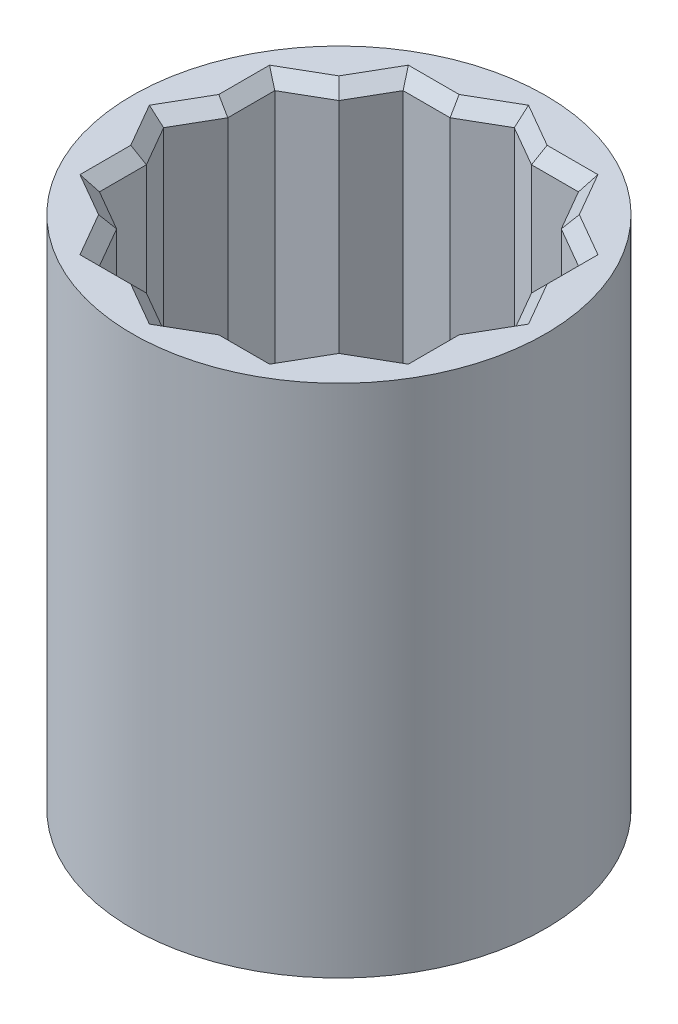
SolidWorks part; units mm, degrees
ref_plane "Front Plane" through (0, 0, 0) normal (0, 0, 1) x (1, 0, 0)
ref_plane "Top Plane" through (0, 0, 0) normal (0, 1, 0) x (1, 0, 0)
ref_plane "Right Plane" through (0, 0, 0) normal (1, 0, 0) x (0, 0, -1)
sketch "Sketch1" plane through (0, 0, 0) normal (0, 1, 0) x (1, 0, 0)
  circle A0 centre (0, 0) radius 9.779
  dimension "Socket_Diameter" = 19.558
extrude "Boss-Extrude1" add sketch "Sketch1" along normal blind 24.384
sketch "Sketch2" plane through (0, 0, 0) normal (0, -1, 0) x (1, 0, 0)
  line L1 (-4.826, 4.826) -> (4.826, 4.826)
  line L2 (-4.826, 4.826) -> (-4.826, -4.826)
  line L3 (-4.826, -4.826) -> (4.826, -4.826)
  line L4 (4.826, 4.826) -> (4.826, -4.826)
  line L5 (-4.826, 4.826) -> (4.826, -4.826) construction
  line L6 (-4.826, -4.826) -> (4.826, 4.826) construction
  point P0 (0, 0)
  dimension "D1" = 9.652
  dimension "D2" = 9.652
extrude "Cut-Extrude1" cut sketch "Sketch2" against normal blind 11.43
sketch "Sketch3" plane through (0, 24.384, 0) normal (0, 1, 0) x (1, 0, 0)
  line L1 (8.3002, 0) -> (4.1501, 7.1882)
  line L2 (4.1501, 7.1882) -> (-4.1501, 7.1882)
  line L3 (-4.1501, 7.1882) -> (-8.3002, 0)
  line L4 (-8.3002, 0) -> (-4.1501, -7.1882)
  line L5 (-4.1501, -7.1882) -> (4.1501, -7.1882)
  line L6 (4.1501, -7.1882) -> (8.3002, 0)
  circle A0 centre (0, 0) radius 7.1882 construction
  dimension "Socket_Size" = 14.3764
extrude "Cut-Extrude2" cut sketch "Sketch3" against normal up to surface (12.954 mm away) up to face at (0, 11.43, 0)
pattern_circular "CirPattern1" count 2 every 30 about axis through (0, 0, 0) along (0, 1, 0) of "Cut-Extrude2"
chamfer "Chamfer1" distance 0.5842 24 edges at (7.1882, 24.384, -3.0381) (7.1882, 24.384, 3.0381) (7.7442, 24.384, -0.963) (7.7442, 24.384, 0.963) (6.2252, 24.384, 4.7061) (0.963, 24.384, 7.7442) (4.7061, 24.384, 6.2252) (3.0381, 24.384, 7.1882) (-0.963, 24.384, 7.7442) (-6.2252, 24.384, 4.7061) (-3.0381, 24.384, 7.1882) (-4.7061, 24.384, 6.2252) (-7.1882, 24.384, 3.0381) (-7.1882, 24.384, -3.0381) (-7.7442, 24.384, 0.963) (-7.7442, 24.384, -0.963) (0.963, 24.384, -7.7442) (6.2252, 24.384, -4.7061) (4.7061, 24.384, -6.2252) (3.0381, 24.384, -7.1882) (-6.2252, 24.384, -4.7061) (-0.963, 24.384, -7.7442) (-3.0381, 24.384, -7.1882) (-4.7061, 24.384, -6.2252)
